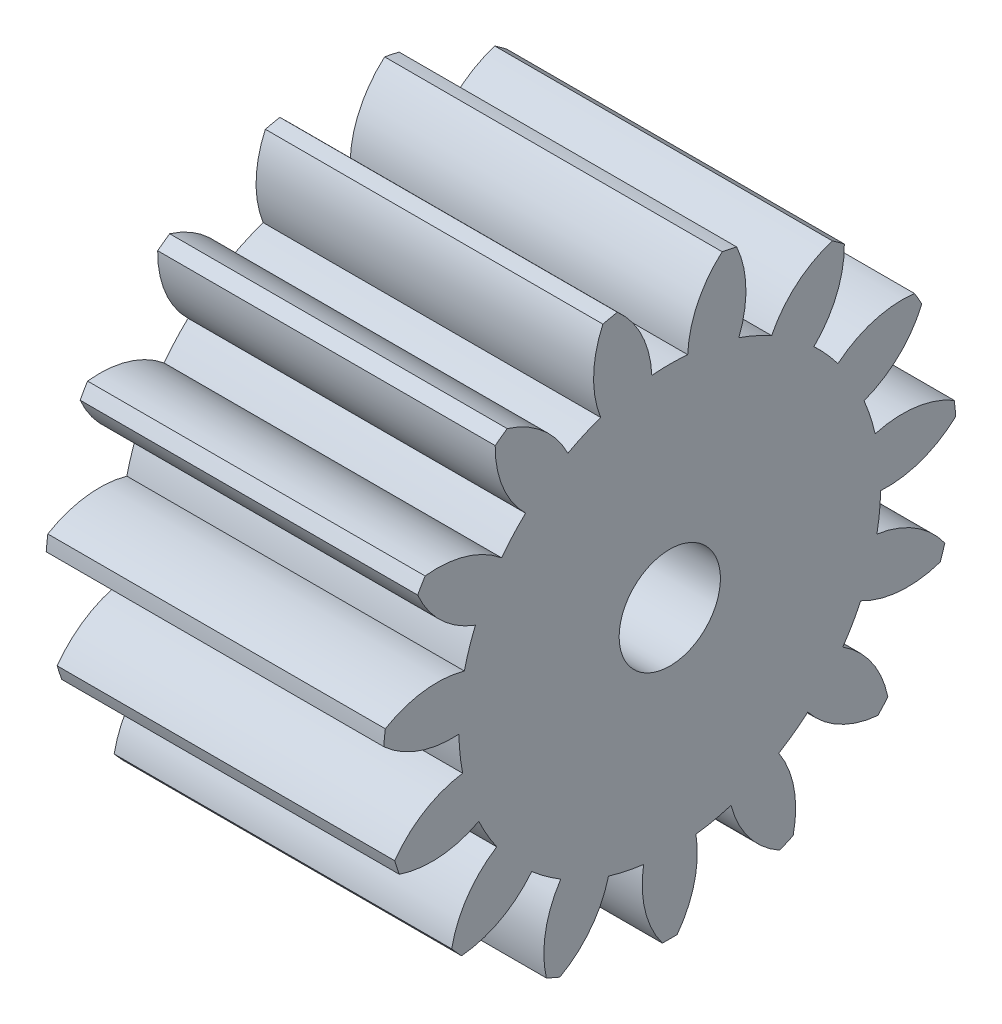
SolidWorks part; units mm, degrees
ref_plane "Plane1" through (0, 0, 0) normal (0, 0, 1) x (1, 0, 0)
ref_plane "Plane2" through (0, 0, 0) normal (0, 1, 0) x (1, 0, 0)
ref_plane "Plane3" through (0, 0, 0) normal (1, 0, 0) x (0, 0, -1)
sketch "HoldingSke" plane through (0, 0, 0) normal (0, 1, 0) x (1, 0, 0)
  line L0 (0, 0) -> (0.9659, -0.2588)
  line L1 (-15, 0) -> (100, 0) construction
  line L2 (0, 0) -> (-2.1039, 2.3779)
  line L3 (0, 0) -> (-11.863, 4.5341)
  line L4 (0, 0) -> (8.3417, 2.2352)
  line L5 (0, 0) -> (-46.8476, -17.4728)
  line L6 (0, 0) -> (-8.2896, -5.593)
  line L7 (-2.1039, 2.3779) -> (8.6586, 51.2059)
  line L8 (-76.2, 54.61) -> (-75.7, 54.61)
  line L9 (-71.009, 38.7566) -> (-53.1078, 45.2721)
  line L10 (-76.2, 71.12) -> (104.1128, 71.12)
  line L11 (0, 0) -> (-10, 0)
  line L12 (-76.2, 101.6) -> (-76.162, 101.6)
  line L13 (24.9733, 27.94) -> (52.9518, 28.4284)
  line L14 (24.9733, 27.94) -> (24.9743, 27.94)
  line L15 (24.9733, 27.94) -> (100.4006, 29.5858)
  line L16 (-63.627, -1) -> (-12.827, -1)
  circle A0 centre (0, 0) radius 1.5
  circle A1 centre (0, 0) radius 6.249
  circle A2 centre (0, 0) radius 37.5
  circle A3 centre (0, 0) radius 1.5
  dimension "MHD" = 12.498
  dimension "Hub_dia" = 75
  dimension "Bore" = 3
  dimension "MBD" = 3
  dimension "Num_teeth" = 15
  dimension "Pitch" = 1
  dimension "Overall_len" = 50
  dimension "Show_teeth" = 15
  dimension "Thickness" = 10
  dimension "OAL" = 50.0001
  dimension "T_dim" = 0.5
  dimension "Ap" = 20
  dimension "H" = 19.05
  dimension "Pitch_radius" = 180.3128
  dimension "Width" = 10
  dimension "Backlash" = 0.038
  dimension "Addendum_fac" = 1
  dimension "Dedendum_fac" = 1.25
  dimension "Clearance_fac" = 0.25
  dimension "Dedendum_add" = 0.001
  dimension "Module" = 1
sketch "BasProSke" plane through (0, 0, 0) normal (0, 1, 0) x (1, 0, 0)
  line L0 (-10, 0) -> (60, 0) construction
  line L1 (0, 0) -> (0, 8.5)
  line L2 (0, 0) -> (10, 0)
  line L3 (10, 0) -> (10, 8.5)
  line L4 (10, 8.5) -> (0, 8.5)
  dimension "Thickness" = 10
  dimension "Diameter" = 17
revolve "Base-Revolve" add sketch "BasProSke" angle 360 about L0
sketch "TooCutSke" plane through (0, 0, 0) normal (1, 0, 0) x (0, 0, -1)
  line L1 (0, 0) -> (0, 107) construction
  line L2 (0, 0) -> (-0.8504, 7.4516) construction
  line L3 (0, 0) -> (-3.1044, 14.6049) construction
  line L4 (-0.8504, 7.4516) -> (-1.5522, 7.3025) construction
  arc A0 (0.5316, 6.2263) -> (-0.5316, 6.2263) centre (0, 0) ccw
  arc A1 (1.5766, 8.3784) -> (-1.5766, 8.3784) centre (0, 0) ccw
  circle A2 centre (0, 0) radius 7.5 construction
  circle A3 centre (0, 0) radius 7.0477 construction
  arc A4 (-0.5316, 6.2263) -> (-1.5766, 8.3784) centre (-3.5289, 6.1005) ccw
  arc A5 (1.5766, 8.3784) -> (0.5316, 6.2263) centre (3.5289, 6.1005) ccw
  dimension "Root_dia" = 12.498
  dimension "Overcut_dia" = 17.0508
  dimension "Pitch_dia" = 15
  dimension "Base_dia" = 14.0954
  dimension "Flank_rad" = 3
  dimension "Half_ang" = 12
  dimension "Half_CT" = 0.7175
extrude "ToothCut" cut sketch "TooCutSke" along normal through all
fillet "Breaks" [suppressed] radius 0.02
fillet "RootFillets" [suppressed] radius 0.251
pattern_circular "TeethCuts" count 15 every 24 about axis through (-10, 0, 0) along (1, 0, 0) of "ToothCut", "RootFillets", "Breaks"
sketch "HubNeaOneSke" plane through (0, 0, 0) normal (-1, 0, 0) x (0, 0, 1)
  circle A0 centre (0, 0) radius 6.249
  dimension "Diameter" = 12.498
extrude "HubNearOne" [suppressed] add sketch "HubNeaOneSke" along normal blind 40.0001
sketch "HubNeaBotSke" plane through (0, 0, 0) normal (-1, 0, 0) x (0, 0, 1)
  circle A0 centre (0, 0) radius 6.249
  dimension "Diameter" = 12.498
extrude "HubNearBoth" [suppressed] add sketch "HubNeaBotSke" along normal blind 20
ref_plane "FarPln" through (10, 0, 0) normal (1, 0, 0) x (0, 0, -1)
sketch "HubFarSke" plane through (10, 0, 0) normal (1, 0, 0) x (0, 0, -1)
  circle A0 centre (0, 0) radius 6.249
  dimension "Diameter" = 12.498
extrude "HubFar" [suppressed] add sketch "HubFarSke" along normal blind 20
sketch "BorSke" plane through (0, 0, 0) normal (1, 0, 0) x (0, 0, -1)
  circle A0 centre (0, 0) radius 1.5
  dimension "Diameter" = 3
extrude "Bore" cut sketch "BorSke" along normal mid plane 100.0001
sketch "KeySke" plane through (0, 0, 0) normal (1, 0, 0) x (0, 0, -1)
  line L0 (-0.6, 0) -> (-0.6, 2)
  line L1 (-0.6, 2) -> (0.6, 2)
  line L2 (0.6, 2) -> (0.6, 0)
  line L3 (0, 0) -> (0, 34) construction
  line L4 (-0.6, 0) -> (0.6, 0)
  dimension "Offset" = 2
  dimension "Width" = 1.2
extrude "Keyway" [suppressed] cut sketch "KeySke" along normal mid plane 100.0001
pattern_circular "Keyway2" [suppressed] count 2 every 90 about axis through (-10, 0, 0) along (1, 0, 0)
equation "' \"Module@HoldingSke\" = 6.35"
equation "' \"Num_teeth@HoldingSke\" = 12"
equation "' \"Ap@HoldingSke\" =  20"
equation "' \"Ap@HoldingSke\" = 20"
equation "' \"Width@HoldingSke\" = 0.5 * 25.4"
equation "' \"Hub_dia@HoldingSke\"= 1 * 25.4"
equation "' \"Hub_dia@HoldingSke\" = 1 * 25.4"
equation "' \"Overall_len@HoldingSke\" = 1.0 * 25.4"
equation "' \"Bore@HoldingSke\" = 0.75 * 25.4"
equation "' \"T_dim@HoldingSke\" = 0.1 * 25.4"
equation "' \"Width@KeySke\" = 0.25 * 25.4"
equation "' \"Show_teeth@HoldingSke\" = 13"
equation "' \"Backlash@HoldingSke\" = 0.009 * 25.4"
equation "' \"Addendum_fac@HoldingSke\" = 1.0"
equation "' \"Dedendum_fac@HoldingSke\" = 1.25"
equation "' \"Dedendum_add@HoldingSke\" = 0.00005 * 25.4"
equation "' \"Clearance_fac@HoldingSke\" = 0.25"
equation "\"Pitch@HoldingSke\" = 1 / \"Module@HoldingSke\""
equation "\"Overcut_dia@TooCutSke\" = (\"Num_teeth@HoldingSke\" + 2 * \"Addendum_fac@HoldingSke\") / \"Pitch@HoldingSke\" + 0.002 * 25.4"
equation "\"Pitch_dia@TooCutSke\" = \"Num_teeth@HoldingSke\" / \"Pitch@HoldingSke\""
equation "\"Base_dia@TooCutSke\" = \"Num_teeth@HoldingSke\" / \"Pitch@HoldingSke\" * cos((\"Ap@HoldingSke\"  * 3.14159265 / 180))"
equation "\"Root_dia@TooCutSke\" = (\"Num_teeth@HoldingSke\" + 2) / \"Pitch@HoldingSke\" - 2 * (\"Addendum_fac@HoldingSke\" + \"Dedendum_fac@HoldingSke\") / \"Pitch@HoldingSke\" - \"Dedendum_add@HoldingSke\" * 2"
equation "\"Half_ang@TooCutSke\" = 180 / \"Num_teeth@HoldingSke\""
equation "\"Half_CT@TooCutSke\" = \"Num_teeth@HoldingSke\" / \"Pitch@HoldingSke\" * sin((3.14159265 / 2 / \"Num_teeth@HoldingSke\")) / 2 - 7 * \"Backlash@HoldingSke\" / 4"
equation "\"Flank_rad@TooCutSke\" = \"Num_teeth@HoldingSke\" / \"Pitch@HoldingSke\" / 5"
equation "\"Radius@RootFillets\" = \"Clearance_fac@HoldingSke\" / \"Pitch@HoldingSke\" + \"Dedendum_add@HoldingSke\""
equation "\"Break_rad@Breaks\" = 0.02 / \"Pitch@HoldingSke\""
equation "\"Thickness@HoldingSke\" = \"Width@HoldingSke\""
equation "\"OAL@HoldingSke\" = \"Thickness@HoldingSke\""
equation "\"MHD@HoldingSke\" = (\"Num_teeth@HoldingSke\" + 2) / \"Pitch@HoldingSke\" - 2 * (\"Addendum_fac@HoldingSke\" + \"Dedendum_fac@HoldingSke\")  / \"Pitch@HoldingSke\" - \"Dedendum_add@HoldingSke\" * 2"
equation "\"MBD@HoldingSke\" = (\"Num_teeth@HoldingSke\" + 2) / \"Pitch@HoldingSke\" - 2 * (\"Addendum_fac@HoldingSke\" + \"Dedendum_fac@HoldingSke\")  / \"Pitch@HoldingSke\" - \"Dedendum_add@HoldingSke\" * 2 - 0.002 * 25.4"
equation "\"MHD@HoldingSke\" = ((sgn( \"MHD@HoldingSke\" - \"Hub_dia@HoldingSke\" )-1)*( \"MHD@HoldingSke\" - \"Hub_dia@HoldingSke\" ))/-2+ \"Hub_dia@HoldingSke\""
equation "\"MBD@HoldingSke\" = ((sgn( \"MBD@HoldingSke\" - \"Bore@HoldingSke\" )-1)*( \"MBD@HoldingSke\" - \"Bore@HoldingSke\" ))/-2+ \"Bore@HoldingSke\""
equation "\"OAL@HoldingSke\" = ((sgn( \"OAL@HoldingSke\" - \"Overall_len@HoldingSke\" )+1)*( \"OAL@HoldingSke\" - \"Overall_len@HoldingSke\" ))/2 + \"Overall_len@HoldingSke\" + 0.000002 * 25.4"
equation "\"Num_teeth@TeethCuts\" = int( \"Show_teeth@HoldingSke\" ) + 1"
equation "\"Num_teeth@TeethCuts\" = ((sgn( \"Num_teeth@TeethCuts\" - \"Num_teeth@HoldingSke\" )-1)*( \"Num_teeth@TeethCuts\" - \"Num_teeth@HoldingSke\" ))/-2+ \"Num_teeth@HoldingSke\""
equation "\"Num_teeth@TeethCuts\" = ((sgn( \"Num_teeth@TeethCuts\" - 2.0)+1)*( \"Num_teeth@TeethCuts\" - 2.0))/2 +2.0"
equation "\"Angle@TeethCuts\" = 360.0 / \"Num_teeth@HoldingSke\""
equation "\"Diameter@BasProSke\" = (\"Num_teeth@HoldingSke\" + 2 * \"Addendum_fac@HoldingSke\") / \"Pitch@HoldingSke\""
equation "\"Thickness@BasProSke\"  = \"Thickness@HoldingSke\""
equation "' \"Fillet_rad@BasProSke\" =  \"Thickness@HoldingSke\" * 0.05"
equation "' \"Fillet_rad@BasProSke\" = \"Thickness@HoldingSke\" * 0.05"
equation "\"MHD@HoldingSke\" = ((sgn( \"MHD@HoldingSke\" - \"Root_dia@TooCutSke\" )-1)*( \"MHD@HoldingSke\" - \"Root_dia@TooCutSke\" ))/-2+ \"Root_dia@TooCutSke\""
equation "\"Diameter@HubNeaOneSke\" = \"MHD@HoldingSke\""
equation "\"Length@HubNearOne\" = \"OAL@HoldingSke\" - \"Thickness@BasProSke\""
equation "\"Diameter@HubNeaBotSke\" = \"MHD@HoldingSke\""
equation "\"Length@HubNearBoth\" = ( \"OAL@HoldingSke\" - \"Thickness@BasProSke\" ) / 2.0"
equation "\"Thickness@FarPln\" = \"Thickness@BasProSke\""
equation "\"Diameter@HubFarSke\" = \"MHD@HoldingSke\""
equation "\"Length@HubFar\" = ( \"OAL@HoldingSke\" - \"Thickness@BasProSke\" ) / 2.0"
equation "\"Diameter@BorSke\" = \"MBD@HoldingSke\""
equation "\"D1@Bore\" = \"OAL@HoldingSke\" * 2.0"
equation "\"D1@Keyway\" = \"OAL@HoldingSke\" * 2.0"
equation "\"Offset@KeySke\" = \"T_dim@HoldingSke\" + \"MBD@HoldingSke\" / 2.0"
